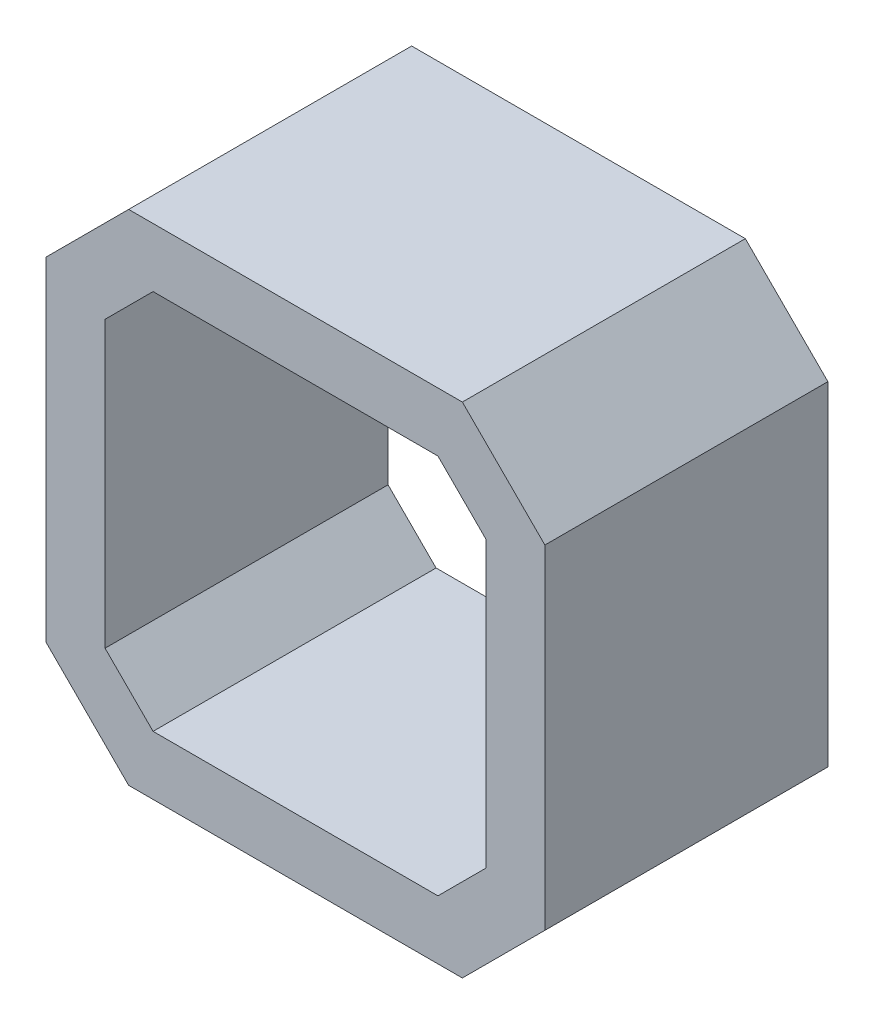
SolidWorks part; units mm, degrees
ref_plane "Front Plane" through (0, 0, 0) normal (0, 0, 1) x (1, 0, 0)
ref_plane "Top Plane" through (0, 0, 0) normal (0, 1, 0) x (1, 0, 0)
ref_plane "Right Plane" through (0, 0, 0) normal (1, 0, 0) x (0, 0, -1)
sketch "Sketch1" plane through (0, 0, 0) normal (0, 0, 1) x (1, 0, 0)
  line L0 (-21.15, 14.15) -> (-14.15, 21.15)
  line L1 (14.15, 21.15) -> (21.15, 14.15)
  line L2 (-14.15, 21.15) -> (14.15, 21.15)
  line L3 (-21.15, 14.15) -> (-21.15, -14.15)
  line L4 (-14.15, -21.15) -> (14.15, -21.15)
  line L5 (21.15, 14.15) -> (21.15, -14.15)
  line L6 (-21.15, 21.15) -> (21.15, -21.15) construction
  line L7 (-21.15, -21.15) -> (21.15, 21.15) construction
  line L8 (14.15, -21.15) -> (21.15, -14.15)
  line L9 (-21.15, -14.15) -> (-14.15, -21.15)
  line L10 (-12.0789, 16.15) -> (12.0789, 16.15)
  line L11 (12.0789, 16.15) -> (16.15, 12.0789)
  line L12 (16.15, 12.0789) -> (16.15, -12.0789)
  line L13 (12.0789, -16.15) -> (16.15, -12.0789)
  line L14 (-12.0789, -16.15) -> (12.0789, -16.15)
  line L15 (-16.15, -12.0789) -> (-12.0789, -16.15)
  line L16 (-16.15, 12.0789) -> (-16.15, -12.0789)
  line L17 (-16.15, 12.0789) -> (-12.0789, 16.15)
  point P1 (0, 0)
  dimension "D1" = 42.3
  dimension "D2" = 5
extrude "Boss-Extrude1" add sketch "Sketch1" along normal blind 24
